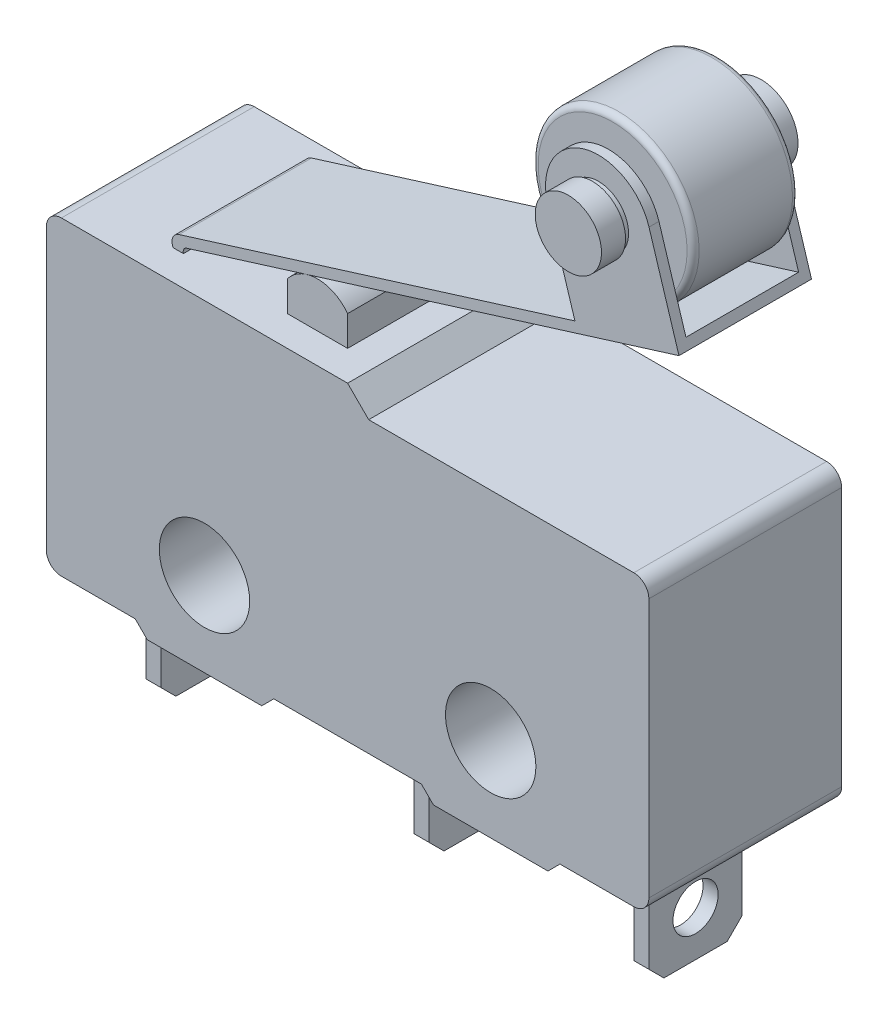
SolidWorks part; units mm, degrees
ref_plane "Plano frontal" through (0, 0, 0) normal (0, 0, 1) x (1, 0, 0)
ref_plane "Plano superior" through (0, 0, 0) normal (0, 1, 0) x (1, 0, 0)
ref_plane "Plano direito" through (0, 0, 0) normal (1, 0, 0) x (0, 0, -1)
sketch "Esboço1" plane through (0, 0, 0) normal (0, 0, 1) x (1, 0, 0)
  line L0 (-3.0235, 7.0803) -> (-2.3235, 6.3803)
  line L1 (3.6265, -3.6197) -> (-0.1735, -3.6197)
  line L2 (6.9765, -2.7197) -> (6.9765, 5.8803)
  line L3 (-3.0235, 7.0803) -> (-12.5235, 7.0803)
  line L4 (-13.0235, -2.7197) -> (-13.0235, 6.5803)
  line L5 (-2.3235, 6.3803) -> (6.4765, 6.3803)
  line L6 (3.6265, -3.6197) -> (4.0265, -3.2197)
  line L7 (4.0265, -3.2197) -> (6.4765, -3.2197)
  line L8 (-0.1735, -3.6197) -> (-0.5735, -3.2197)
  line L9 (-0.5735, -3.2197) -> (-5.4735, -3.2197)
  line L11 (-12.5235, -3.2197) -> (-10.0735, -3.2197)
  line L12 (-10.0735, -3.2197) -> (-9.6735, -3.6197)
  line L13 (-5.8735, -3.6197) -> (-9.6735, -3.6197)
  line L14 (-7.7735, -3.6197) -> (-7.7735, -0.8197) construction
  line L15 (1.7265, -3.6197) -> (1.7265, -0.8197) construction
  line L16 (-11.1235, -6.9197) -> (-11.1235, -6.0187) construction
  line L17 (-11.3735, -3.2197) -> (-10.8735, -3.2197)
  line L18 (-11.3735, -3.2197) -> (-11.3735, -6.9197)
  line L19 (-11.3735, -6.9197) -> (-10.8735, -6.9197)
  line L20 (-10.8735, -3.2197) -> (-10.8735, -6.9197)
  line L21 (-2.4735, -3.2197) -> (-1.9735, -3.2197)
  line L22 (-2.4735, -3.2197) -> (-2.4735, -6.9197)
  line L23 (-2.4735, -6.9197) -> (-1.9735, -6.9197)
  line L24 (-1.9735, -3.2197) -> (-1.9735, -6.9197)
  line L25 (4.8265, -3.2197) -> (5.3265, -3.2197)
  line L26 (4.8265, -3.2197) -> (4.8265, -6.9197)
  line L27 (4.8265, -6.9197) -> (5.3265, -6.9197)
  line L28 (5.3265, -3.2197) -> (5.3265, -6.9197)
  line L29 (-11.1235, -6.0187) -> (-10.8735, -6.0187) construction
  line L30 (-2.2235, -6.9197) -> (-2.2235, -6.0187) construction
  line L31 (5.0765, -6.9197) -> (5.0765, -6.0187) construction
  line L32 (-2.4735, -6.0187) -> (-1.9735, -6.0187) construction
  line L33 (4.8265, -6.0187) -> (5.3265, -6.0187) construction
  line L34 (-10.0735, -0.8197) -> (-10.0735, -3.2197)
  line L35 (-5.4735, -0.8197) -> (-5.4735, -3.2197)
  line L36 (-0.5735, -0.8197) -> (-0.5735, -3.2197)
  line L37 (4.0265, -0.8197) -> (4.0265, -3.2197)
  line L38 (-5.4735, -3.2197) -> (-5.8735, -3.6197)
  line L39 (-13.0235, 6.5803) -> (-13.0235, 23.1562) construction
  line L40 (-4.0235, 7.0803) -> (-6.0235, 7.0803)
  line L41 (-4.0235, 7.0803) -> (-4.0235, 8.0803)
  line L43 (-6.0235, 7.0803) -> (-6.0235, 8.0803)
  line L45 (6.9765, 23.1562) -> (6.9765, 5.8803) construction
  line L46 (-9.3654, 7.2891) -> (6.9765, 12.371)
  line L47 (-6.0235, 8.0803) -> (-4.0235, 8.0803) construction
  line L48 (-5.0235, 8.5803) -> (-5.0235, 8.0803) construction
  line L49 (-9.4739, 7.0826) -> (-9.4732, 7.0803)
  line L50 (6.9765, 12.371) -> (5.9817, 15.5699)
  line L51 (-9.8188, 7.0803) -> (-9.838, 7.1421)
  line L52 (-9.6209, 7.5553) -> (3.5229, 11.6426)
  line L53 (-9.8235, 5.611) -> (-9.8235, 8.1824) construction
  line L55 (2.6261, 14.5264) -> (3.5229, 11.6426)
  circle A0 centre (-7.7735, -0.8197) radius 1.5
  circle A1 centre (1.7265, -0.8197) radius 1.5
  arc A2 (-5.4735, -0.8197) -> (-10.0735, -0.8197) centre (-7.7735, -0.8197) ccw
  arc A3 (4.0265, -0.8197) -> (-0.5735, -0.8197) centre (1.7265, -0.8197) ccw
  arc A4 (6.9765, 5.8803) -> (6.4765, 6.3803) centre (6.4765, 5.8803) ccw
  arc A5 (-12.5235, 7.0803) -> (-13.0235, 6.5803) centre (-12.5235, 6.5803) ccw
  arc A6 (6.9765, -2.7197) -> (6.4765, -3.2197) centre (6.4765, -2.7197) cw
  arc A7 (-12.5235, -3.2197) -> (-13.0235, -2.7197) centre (-12.5235, -2.7197) cw
  arc A10 (-6.0235, 8.0803) -> (-4.0235, 8.0803) centre (-5.0235, 7.3303) cw
  arc A11 (-9.4739, 7.0826) -> (-9.3654, 7.2891) centre (-9.3164, 7.1316) cw
  arc A12 (-9.838, 7.1421) -> (-9.6209, 7.5553) centre (-9.5229, 7.2401) cw
  arc A14 (5.9817, 15.5699) -> (2.6261, 14.5264) centre (4.3039, 15.0482) ccw
  circle A15 centre (4.3039, 15.0482) radius 2.6726
  point P0 (0, 0)
  point P63 (-4.0235, 8.5803)
  point P66 (-6.0235, 8.5803)
  dimension "D3" = 3
  dimension "D4" = 3
  dimension "D7" = 9.5
  dimension "D22" = 4.6
  dimension "D23" = 4.6
  dimension "D15" = 0.5
  dimension "D26" = 1
  dimension "D31" = 1.25
  dimension "D35" = 0.165
  dimension "D36" = 0.33
  dimension "D1" = 10.7
  dimension "D2" = 9.6
  dimension "D5" = 2.8
  dimension "D6" = 2.8
  dimension "D8" = 0.5
  dimension "D9" = 0.5
  dimension "D10" = 0.5
  dimension "D11" = 16.2
  dimension "D12" = 7.3
  dimension "D13" = 14
  dimension "D14" = 10
  dimension "D16" = 135
  dimension "D17" = 135
  dimension "D18" = 1
  dimension "D19" = 135
  dimension "D20" = 5.25
  dimension "D21" = 20
  dimension "D24" = 2
  dimension "D25" = 1.5
  dimension "D27" = 10
  dimension "D28" = 1.65
  dimension "D29" = 0.5
  dimension "D30" = 2
  dimension "D33" = 3.2
  dimension "D34" = 0.33
sketch "Esboço2" plane through (0, 0, 0) normal (0, 0, 1) x (1, 0, 0)
  line L0 (4.0265, -3.2197) -> (6.4765, -3.2197) construction
  line L1 (3.6265, -3.6197) -> (4.0265, -3.2197) construction
  line L2 (3.6265, -3.6197) -> (-0.1735, -3.6197) construction
  line L3 (-0.1735, -3.6197) -> (-0.5735, -3.2197) construction
  line L4 (-5.4735, -3.2197) -> (-5.8735, -3.6197) construction
  line L5 (-0.5735, -3.2197) -> (-5.4735, -3.2197) construction
  line L6 (-5.8735, -3.6197) -> (-9.6735, -3.6197) construction
  line L7 (-10.0735, -3.2197) -> (-9.6735, -3.6197) construction
  line L8 (-12.5235, -3.2197) -> (-10.0735, -3.2197) construction
  line L9 (6.9765, -2.7197) -> (6.9765, 5.8803) construction
  line L10 (-2.3235, 6.3803) -> (6.4765, 6.3803) construction
  line L11 (-3.0235, 7.0803) -> (-2.3235, 6.3803) construction
  line L12 (-13.0235, -2.7197) -> (-13.0235, 6.5803) construction
  line L13 (-3.0235, 7.0803) -> (-12.5235, 7.0803) construction
  line L14 (4.0265, -3.2197) -> (6.4765, -3.2197)
  line L15 (3.6265, -3.6197) -> (4.0265, -3.2197)
  line L16 (3.6265, -3.6197) -> (-0.1735, -3.6197)
  line L17 (-0.1735, -3.6197) -> (-0.5735, -3.2197)
  line L18 (-5.4735, -3.2197) -> (-5.8735, -3.6197)
  line L19 (-0.5735, -3.2197) -> (-5.4735, -3.2197)
  line L20 (-5.8735, -3.6197) -> (-9.6735, -3.6197)
  line L21 (-10.0735, -3.2197) -> (-9.6735, -3.6197)
  line L22 (-12.5235, -3.2197) -> (-10.0735, -3.2197)
  line L23 (6.9765, -2.7197) -> (6.9765, 5.8803)
  line L24 (-2.3235, 6.3803) -> (6.4765, 6.3803)
  line L25 (-3.0235, 7.0803) -> (-2.3235, 6.3803)
  line L26 (-13.0235, -2.7197) -> (-13.0235, 6.5803)
  line L27 (-3.0235, 7.0803) -> (-12.5235, 7.0803)
  circle A0 centre (1.7265, -0.8197) radius 1.5 construction
  circle A1 centre (-7.7735, -0.8197) radius 1.5 construction
  arc A2 (6.4765, -3.2197) -> (6.9765, -2.7197) centre (6.4765, -2.7197) ccw construction
  arc A3 (-13.0235, -2.7197) -> (-12.5235, -3.2197) centre (-12.5235, -2.7197) ccw construction
  arc A4 (6.9765, 5.8803) -> (6.4765, 6.3803) centre (6.4765, 5.8803) ccw construction
  arc A5 (-12.5235, 7.0803) -> (-13.0235, 6.5803) centre (-12.5235, 6.5803) ccw construction
  circle A6 centre (1.7265, -0.8197) radius 1.5
  circle A7 centre (-7.7735, -0.8197) radius 1.5
  arc A8 (6.4765, -3.2197) -> (6.9765, -2.7197) centre (6.4765, -2.7197) ccw
  arc A9 (-13.0235, -2.7197) -> (-12.5235, -3.2197) centre (-12.5235, -2.7197) ccw
  arc A10 (6.9765, 5.8803) -> (6.4765, 6.3803) centre (6.4765, 5.8803) ccw
  arc A11 (-12.5235, 7.0803) -> (-13.0235, 6.5803) centre (-12.5235, 6.5803) ccw
extrude "Ressalto-extrusão1" add sketch "Esboço2" along normal blind 6.4
ref_plane "Plano1" through (0, 0, 1) normal (0, 0, -1) x (-1, 0, 0)
sketch "Esboço3" plane through (0, 0, 1) normal (0, 0, -1) x (-1, 0, 0)
  line L0 (3.0235, 7.0803) -> (12.5235, 7.0803) construction
  line L1 (6.0235, 7.0803) -> (6.0235, 8.0803) construction
  line L2 (4.0235, 7.0803) -> (4.0235, 8.0803) construction
  line L3 (4.0235, 7.0803) -> (6.0235, 7.0803)
  line L4 (6.0235, 7.0803) -> (6.0235, 8.0803)
  line L5 (4.0235, 7.0803) -> (4.0235, 8.0803)
  arc A0 (6.0235, 8.0803) -> (4.0235, 8.0803) centre (5.0235, 7.3303) ccw construction
  arc A1 (6.0235, 8.0803) -> (4.0235, 8.0803) centre (5.0235, 7.3303) ccw
extrude "Ressalto-extrusão2" add sketch "Esboço3" against normal blind 4.4
ref_plane "Plano2" through (0, 0, 1.65) normal (0, 0, -1) x (-1, 0, 0)
sketch "Esboço4" plane through (0, 0, 1.65) normal (0, 0, -1) x (-1, 0, 0)
  line L0 (11.3735, -6.9197) -> (10.8735, -6.9197) construction
  line L1 (11.3735, -3.2197) -> (11.3735, -6.9197) construction
  line L2 (10.8735, -3.2197) -> (10.8735, -6.9197) construction
  line L3 (12.5235, -3.2197) -> (10.0735, -3.2197) construction
  line L4 (2.4735, -6.9197) -> (1.9735, -6.9197) construction
  line L5 (1.9735, -3.2197) -> (1.9735, -6.9197) construction
  line L6 (2.4735, -3.2197) -> (2.4735, -6.9197) construction
  line L7 (0.5735, -3.2197) -> (5.4735, -3.2197) construction
  line L8 (-4.8265, -6.9197) -> (-5.3265, -6.9197) construction
  line L9 (-4.8265, -3.2197) -> (-4.8265, -6.9197) construction
  line L10 (-5.3265, -3.2197) -> (-5.3265, -6.9197) construction
  line L11 (-4.0265, -3.2197) -> (-6.4765, -3.2197) construction
  line L12 (11.3735, -6.9197) -> (10.8735, -6.9197)
  line L13 (11.3735, -3.2197) -> (11.3735, -6.9197)
  line L14 (10.8735, -3.2197) -> (10.8735, -6.9197)
  line L15 (11.3735, -3.2197) -> (10.8735, -3.2197)
  line L16 (2.4735, -6.9197) -> (1.9735, -6.9197)
  line L17 (1.9735, -3.2197) -> (1.9735, -6.9197)
  line L18 (2.4735, -3.2197) -> (2.4735, -6.9197)
  line L19 (1.9735, -3.2197) -> (2.4735, -3.2197)
  line L20 (-4.8265, -6.9197) -> (-5.3265, -6.9197)
  line L21 (-4.8265, -3.2197) -> (-4.8265, -6.9197)
  line L22 (-5.3265, -3.2197) -> (-5.3265, -6.9197)
  line L23 (-4.8265, -3.2197) -> (-5.3265, -3.2197)
extrude "Ressalto-extrusão4" add sketch "Esboço4" against normal blind 3.1
sketch "Esboço6" plane through (-11.3735, 0, 0) normal (-1, 0, 0) x (0, 0, 1)
  line L0 (1.65, -6.4197) -> (2.15, -6.9197)
  line L1 (4.25, -6.9197) -> (4.75, -6.4197)
  line L2 (0.9374, -4.3072) -> (1.65, -4.3072)
  line L3 (5.4186, -4.3072) -> (5.4186, -7.7793)
  line L4 (1.65, -3.2197) -> (1.65, -6.9197)
  line L5 (1.65, -6.9197) -> (4.75, -6.9197)
  line L6 (4.75, -6.9197) -> (4.75, -3.2197)
  line L7 (4.75, -3.2197) -> (1.65, -3.2197)
  line L8 (1.65, -4.3072) -> (1.65, -6.4197)
  line L9 (2.15, -6.9197) -> (4.25, -6.9197)
  line L10 (4.75, -6.4197) -> (4.75, -4.3072)
  line L12 (5.4186, -7.7793) -> (0.9374, -7.7793)
  line L13 (0.9374, -7.7793) -> (0.9374, -4.3072)
  line L14 (4.75, -4.3072) -> (5.4186, -4.3072)
  circle A0 centre (3.2, -5.4197) radius 0.75
  dimension "D2" = 1.5
  dimension "D3" = 1.5
  dimension "D1" = 0
extrude "Corte-extrusão1" cut sketch "Esboço6" against normal blind 23.1
sketch "Esboço7" plane through (0, 0, 1) normal (0, 0, -1) x (-1, 0, 0)
  line L0 (9.8188, 7.0803) -> (9.838, 7.1421) construction
  line L1 (9.3654, 7.2891) -> (-6.9765, 12.371)
  line L4 (9.8188, 7.0803) -> (9.838, 7.1421)
  line L8 (9.4739, 7.0826) -> (9.4732, 7.0803) construction
  line L9 (9.4739, 7.0826) -> (9.4732, 7.0803)
  line L10 (-6.9765, 12.371) -> (-5.9817, 15.5699) construction
  line L11 (-6.9765, 12.371) -> (-6.8785, 12.6861)
  line L13 (9.4732, 7.0803) -> (9.8188, 7.0803)
  line L14 (9.6209, 7.5553) -> (-6.8785, 12.6861)
  arc A0 (9.838, 7.1421) -> (9.6209, 7.5553) centre (9.5229, 7.2401) ccw construction
  arc A1 (9.4739, 7.0826) -> (9.3654, 7.2891) centre (9.3164, 7.1316) ccw construction
  arc A2 (9.838, 7.1421) -> (9.6209, 7.5553) centre (9.5229, 7.2401) ccw
  arc A3 (9.4739, 7.0826) -> (9.3654, 7.2891) centre (9.3164, 7.1316) ccw
  point P0 (9.8188, 7.0803)
extrude "Ressalto-extrusão15" add sketch "Esboço7" against normal blind 4.4 separate body
sketch "Esboço8" plane through (0, 0, 1) normal (0, 0, -1) x (-1, 0, 0)
  line L0 (9.6209, 7.5553) -> (-6.8785, 12.6861) construction
  line L1 (-2.6261, 14.5264) -> (-3.5229, 11.6426) construction
  line L2 (-6.9765, 12.371) -> (-5.9817, 15.5699) construction
  line L3 (-3.5229, 11.6426) -> (-6.8785, 12.6861)
  line L4 (-2.6261, 14.5264) -> (-3.5229, 11.6426)
  line L5 (-6.8785, 12.6861) -> (-5.9817, 15.5699)
  arc A0 (-2.6261, 14.5264) -> (-5.9817, 15.5699) centre (-4.3039, 15.0482) ccw construction
  arc A1 (-2.6261, 14.5264) -> (-5.9817, 15.5699) centre (-4.3039, 15.0482) ccw
extrude "Ressalto-extrusão16" add sketch "Esboço8" against normal blind 0.33
sketch "Esboço9" plane through (0, 0, 5.4) normal (0, 0, 1) x (1, 0, 0)
  line L3 (6.8785, 12.6861) -> (5.9817, 15.5699)
  line L4 (2.6261, 14.5264) -> (3.5229, 11.6426)
  line L5 (3.5229, 11.6426) -> (6.8785, 12.6861)
  line L6 (6.8785, 12.6861) -> (5.9817, 15.5699)
  line L7 (2.6261, 14.5264) -> (3.5229, 11.6426)
  line L8 (3.5229, 11.6426) -> (6.8785, 12.6861)
  arc A1 (5.9817, 15.5699) -> (2.6261, 14.5264) centre (4.3039, 15.0482) ccw
  arc A2 (5.9817, 15.5699) -> (2.6261, 14.5264) centre (4.3039, 15.0482) ccw
  dimension "D1" = 0
extrude "Ressalto-extrusão17" add sketch "Esboço9" against normal blind 0.33
sketch "Esboço10" plane through (0, 0, 6.4) normal (0, 0, 1) x (1, 0, 0)
  circle A0 centre (4.3039, 15.0482) radius 1
  dimension "D1" = 2
extrude "Ressalto-extrusão18" add sketch "Esboço10" against normal up to surface (6.4 mm away)
sketch "Esboço11" plane through (0, 0, 0) normal (0, 0, -1) x (-1, 0, 0)
  circle A0 centre (-4.3039, 15.0482) radius 1.225
  dimension "D1" = 2.45
extrude "Ressalto-extrusão19" add sketch "Esboço11" against normal blind 0.8
sketch "Esboço12" plane through (0, 0, 6.4) normal (0, 0, 1) x (1, 0, 0)
  circle A0 centre (4.3039, 15.0482) radius 1.1
  dimension "D1" = 2.2
extrude "Ressalto-extrusão20" add sketch "Esboço12" against normal blind 0.8
ref_plane "Plano3" through (0, 0, 1.43) normal (0, 0, 1) x (1, 0, 0)
sketch "Esboço13" plane through (0, 0, 1.43) normal (0, 0, 1) x (1, 0, 0)
  circle A0 centre (4.3039, 15.0482) radius 2.6726
extrude "Ressalto-extrusão21" add sketch "Esboço13" along normal blind 3.5
fillet "Filete1" radius 0.2 2 edges at (6.9765, 15.0482, 4.93) (6.9765, 15.0482, 1.43)
